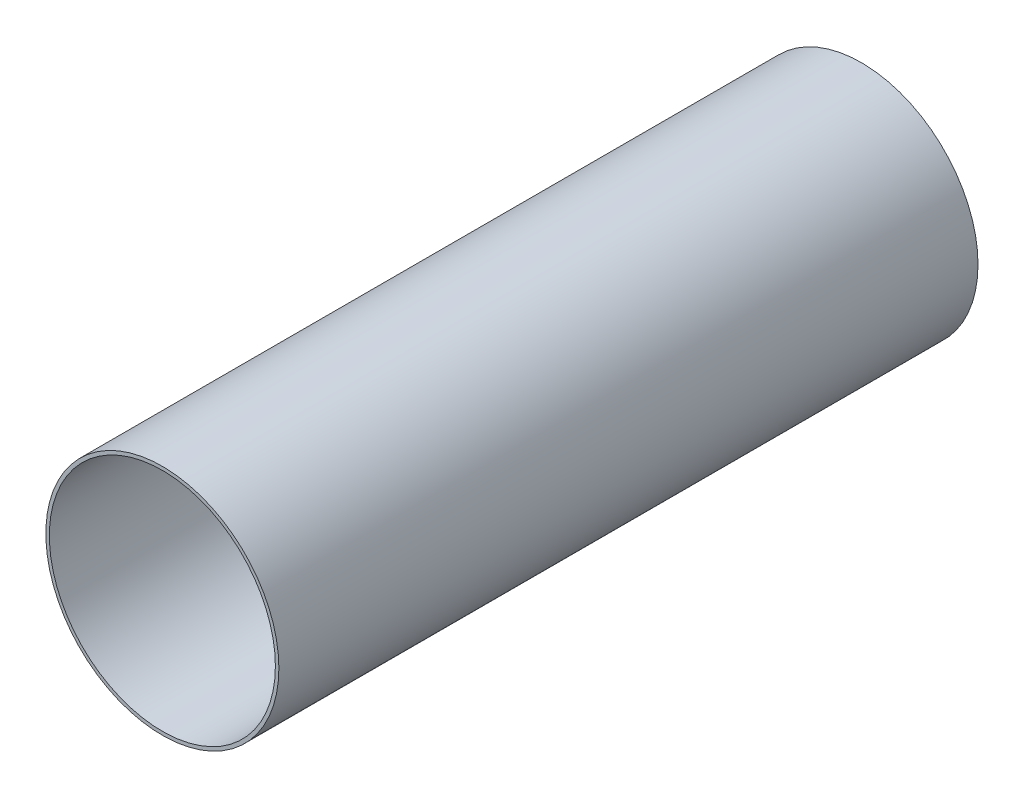
SolidWorks part; units mm, degrees
material "PVC Rígido"
ref_plane "Plano frontal" through (0, 0, 0) normal (0, 0, 1) x (1, 0, 0)
ref_plane "Plano superior" through (0, 0, 0) normal (0, 1, 0) x (1, 0, 0)
ref_plane "Plano direito" through (0, 0, 0) normal (1, 0, 0) x (0, 0, -1)
sketch "Esboço1" plane through (0, 0, 0) normal (0, 0, 1) x (1, 0, 0)
  circle A0 centre (0, 0) radius 50
  dimension "D1" = 100
extrude "Ressalto-extrusão1" add sketch "Esboço1" along normal blind 300
shell "Casca2" thickness 1.5
